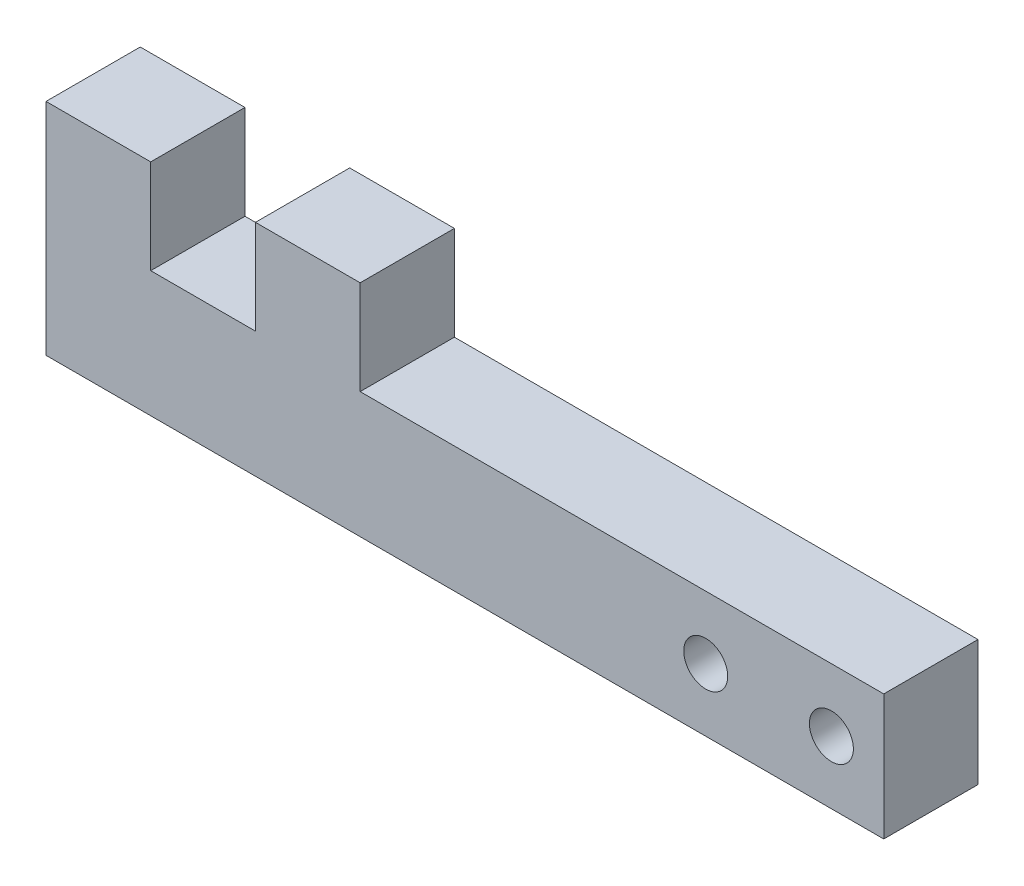
SolidWorks part; units mm, degrees
ref_plane "Front" through (0, 0, 0) normal (0, 0, 1) x (1, 0, 0)
ref_plane "Top" through (0, 0, 0) normal (0, 1, 0) x (1, 0, 0)
ref_plane "Right" through (0, 0, 0) normal (1, 0, 0) x (0, 0, -1)
sketch "Esquisse1" plane through (0, 0, 0) normal (0, 0, 1) x (1, 0, 0)
  line L1 (0, 0) -> (80, 0)
  line L2 (0, 0) -> (0, 12)
  line L3 (0, 12) -> (80, 12)
  line L4 (80, 0) -> (80, 12)
  dimension "D1" = 12
  dimension "D2" = 80
extrude "Boss.-Extru.1" add sketch "Esquisse1" along normal blind 9
sketch "Esquisse2" plane through (0, 0, 9) normal (0, 0, 1) x (1, 0, 0)
  line L0 (80, 12) -> (0, 12) construction
  line L1 (0, 12) -> (10, 12)
  line L2 (0, 12) -> (0, 21)
  line L3 (0, 21) -> (10, 21)
  line L4 (10, 12) -> (10, 21)
  line L5 (20, 12) -> (30, 12)
  line L6 (20, 12) -> (20, 21)
  line L7 (20, 21) -> (30, 21)
  line L8 (30, 12) -> (30, 21)
  dimension "D1" = 10
  dimension "D2" = 9
  dimension "D3" = 10
extrude "Boss.-Extru.2" add sketch "Esquisse2" against normal up to vertex (9 mm away)
sketch "Esquisse3" plane through (0, 0, 9) normal (0, 0, 1) x (1, 0, 0)
  line L0 (80, 6) -> (63, 6) construction
  line L1 (80, 0) -> (80, 12) construction
  circle A0 centre (63, 6) radius 2.1
  circle A1 centre (75, 6) radius 2.1
  dimension "D1" = 4.2
  dimension "D2" = 12
  dimension "D3" = 5
extrude "Enlèv. mat.-Extru.1" cut sketch "Esquisse3" against normal through all
